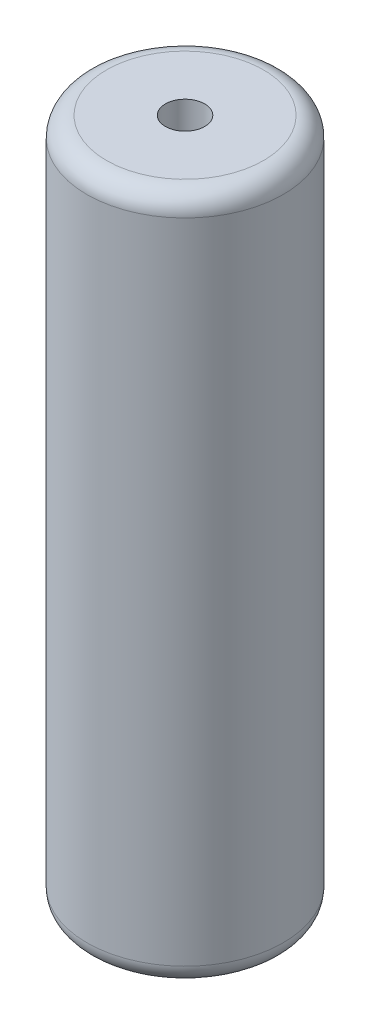
SolidWorks part; units mm, degrees
material "Alumina"
ref_plane "Front Plane" through (0, 0, 0) normal (0, 0, 1) x (1, 0, 0)
ref_plane "Top Plane" through (0, 0, 0) normal (0, 1, 0) x (1, 0, 0)
ref_plane "Right Plane" through (0, 0, 0) normal (1, 0, 0) x (0, 0, -1)
sketch "Sketch1" plane through (0, 0, 0) normal (0, 1, 0) x (1, 0, 0)
  circle A0 centre (0, 0) radius 10
  dimension "D1" = 20
extrude "Boss-Extrude1" add sketch "Sketch1" along normal blind 70
sketch "Sketch2" plane through (0, 70, 0) normal (0, 1, 0) x (1, 0, 0)
  circle A0 centre (0, 0) radius 2
  dimension "D1" = 4
extrude "Cut-Extrude1" cut sketch "Sketch2" against normal blind 60
fillet "Fillet1" radius 2 2 edges at (0, 0, 10) (0, 70, 10)
sketch "Sketch4" plane through (0, 0, 0) normal (0, -1, 0) x (1, 0, 0)
  circle A0 centre (0, 0) radius 2
  dimension "D1" = 4
extrude "Cut-Extrude2" cut sketch "Sketch4" against normal blind 5
